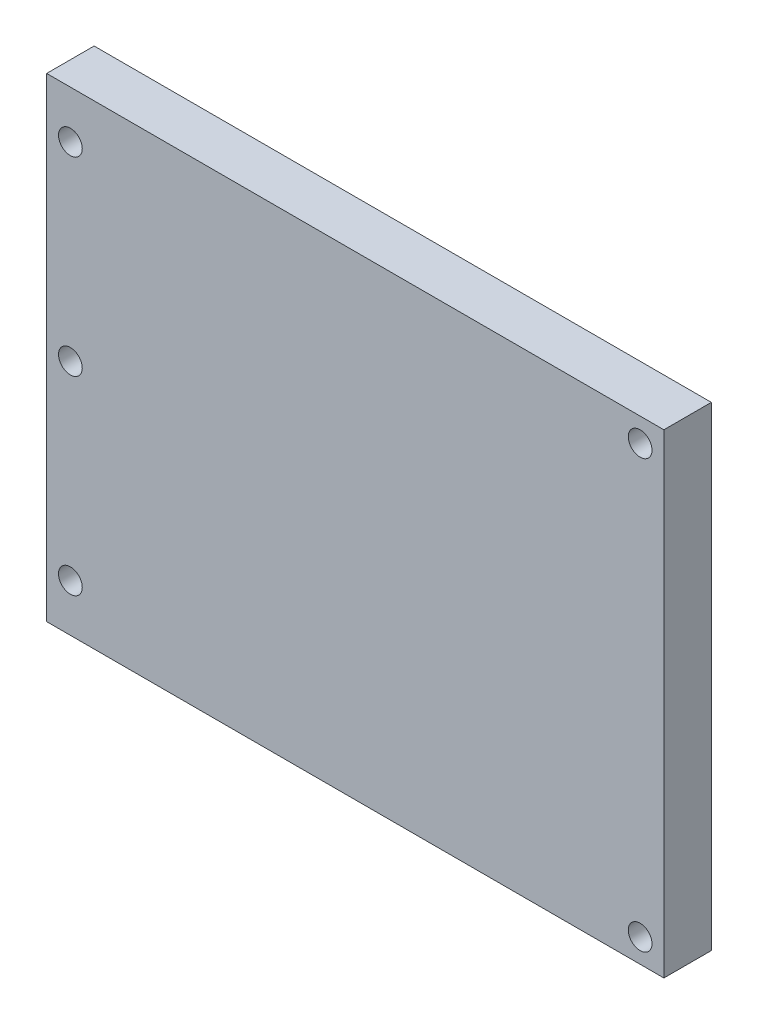
SolidWorks part; units mm, degrees
ref_plane "前视基准面" through (0, 0, 0) normal (0, 0, 1) x (1, 0, 0)
ref_plane "上视基准面" through (0, 0, 0) normal (0, 1, 0) x (1, 0, 0)
ref_plane "右视基准面" through (0, 0, 0) normal (1, 0, 0) x (0, 0, -1)
sketch "草图1" plane through (0, 0, 0) normal (0, 0, 1) x (1, 0, 0)
  line L1 (-40, 20) -> (40, 20)
  line L2 (-40, 20) -> (-40, -20)
  line L3 (-40, -20) -> (40, -20)
  line L4 (40, 20) -> (40, -20)
  line L5 (-40, 20) -> (40, -20) construction
  line L6 (-40, -20) -> (40, 20) construction
  point P0 (0, 0)
extrude "凸台-拉伸2" add sketch "草图1" along normal blind 10
sketch "草图2" plane through (0, 0, 10) normal (0, 0, 1) x (1, 0, 0)
  line L2 (-40, -20) -> (40, -20) construction
  circle A0 centre (35, -15) radius 2.5
  circle A1 centre (35, 15) radius 2.5
  dimension "D2" = 5
sketch "草图4" plane through (-40, 0, 0) normal (-1, 0, 0) x (0, 0, 1)
  line L0 (0, 20) -> (10, 20)
  line L1 (10, 20) -> (10, -20)
  line L2 (10, -20) -> (0, -20)
  line L3 (0, -20) -> (0, 20)
extrude "凸台-拉伸3" add sketch "草图4" along normal blind 50
sketch "草图5" plane through (0, 0, 10) normal (0, 0, 1) x (1, 0, 0)
  line L0 (-90, 0) -> (-85, 0)
  line L1 (-90, -20) -> (-90, 20) construction
  circle A0 centre (-85, 0) radius 2.5
extrude "切除-拉伸2" cut sketch "草图5" against normal through all
sketch "草图6" plane through (0, -20, 0) normal (0, -1, 0) x (1, 0, 0)
  line L0 (-90, 10) -> (-90, 0)
  line L1 (-90, 0) -> (40, 0)
  line L2 (40, 0) -> (40, 10)
  line L3 (40, 10) -> (-90, 10)
extrude "凸台-拉伸4" add sketch "草图6" along normal blind 30
sketch "草图7" plane through (0, 20, 0) normal (0, 1, 0) x (1, 0, 0)
  line L0 (-90, -10) -> (-90, 0)
  line L1 (-90, 0) -> (40, 0)
  line L2 (40, 0) -> (40, -10)
  line L3 (40, -10) -> (-90, -10)
extrude "凸台-拉伸5" add sketch "草图7" along normal blind 30
sketch "草图8" plane through (0, 0, 10) normal (0, 0, 1) x (1, 0, 0)
  line L0 (40, 0) -> (30, 0)
  line L1 (40, -50) -> (40, 50) construction
  line L2 (35, 0) -> (35, -45)
  circle A0 centre (35, -45) radius 2.5
  circle A1 centre (35, 45) radius 2.5
extrude "切除-拉伸3" cut sketch "草图8" against normal through all contours A1 | A0
sketch "草图10" plane through (0, 0, 10) normal (0, 0, 1) x (1, 0, 0)
  line L0 (-85, 0) -> (-90, 0)
  line L1 (-90, -50) -> (-90, 50) construction
  circle A0 centre (-85, 40) radius 2.5
  circle A1 centre (-85, -40) radius 2.5
extrude "切除-拉伸4" cut sketch "草图10" against normal through all contours A0 | A1
